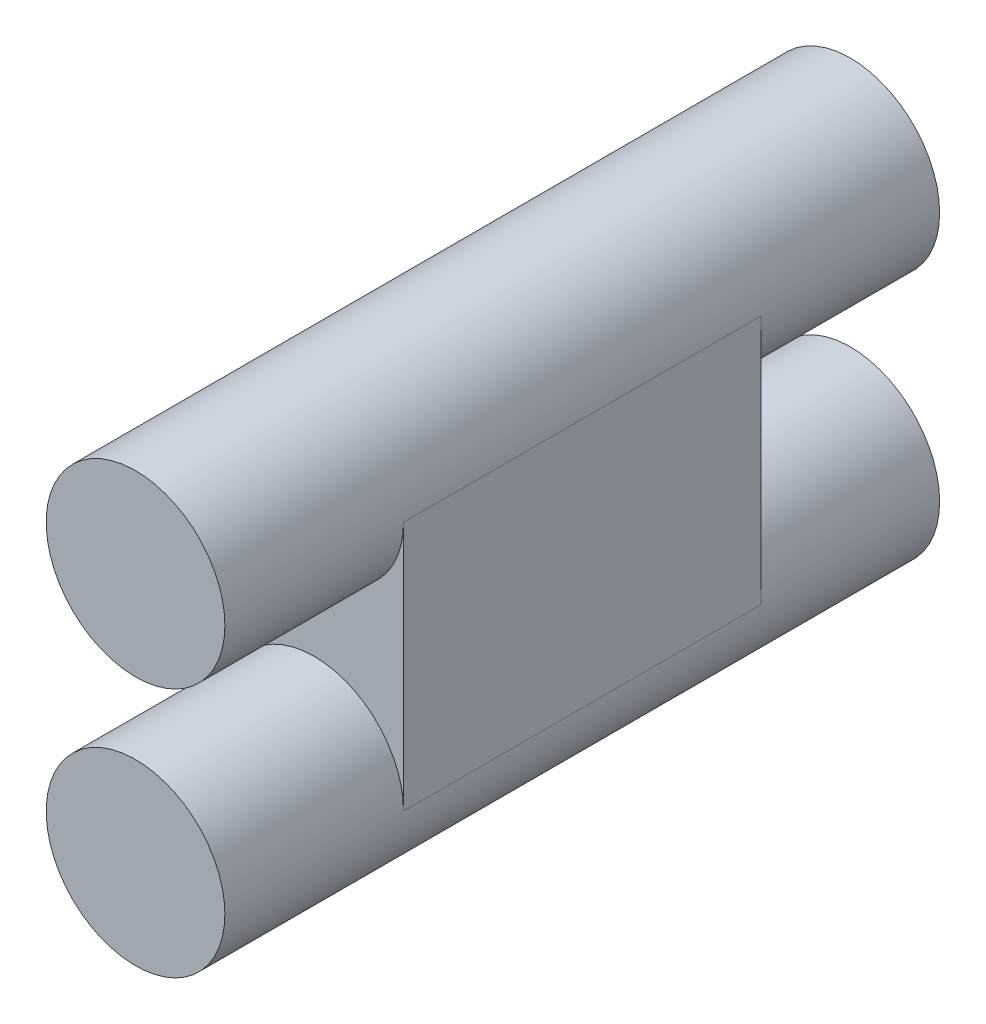
SolidWorks part; units mm, degrees
ref_plane "Front Plane" through (0, 0, 0) normal (0, 0, 1) x (1, 0, 0)
ref_plane "Top Plane" through (0, 0, 0) normal (0, 1, 0) x (1, 0, 0)
ref_plane "Right Plane" through (0, 0, 0) normal (1, 0, 0) x (0, 0, -1)
sketch "Sketch1" plane through (0, 0, 0) normal (0, 1, 0) x (1, 0, 0)
  line L1 (0, 0) -> (10, 0)
  line L2 (0, 0) -> (0, -10)
  line L3 (0, -10) -> (10, -10)
  line L4 (10, 0) -> (10, -10)
  dimension "D1" = 10
  dimension "D2" = 10
extrude "Boss-Extrude1" add sketch "Sketch1" along normal blind 14
sketch "Sketch2" plane through (0, 0, 0) normal (0, 0, 1) x (1, 0, 0)
  line L0 (0, 14) -> (10, 14) construction
  line L1 (0, 0) -> (10, 0) construction
  circle A0 centre (5, 14) radius 5
  circle A1 centre (5, 0) radius 5
extrude "Boss-Extrude2" add sketch "Sketch2" along normal blind 20
mirror "Mirror1" about plane through (0, 14, 0) normal (0, 0, 1) of "Boss-Extrude2", "Boss-Extrude1"
